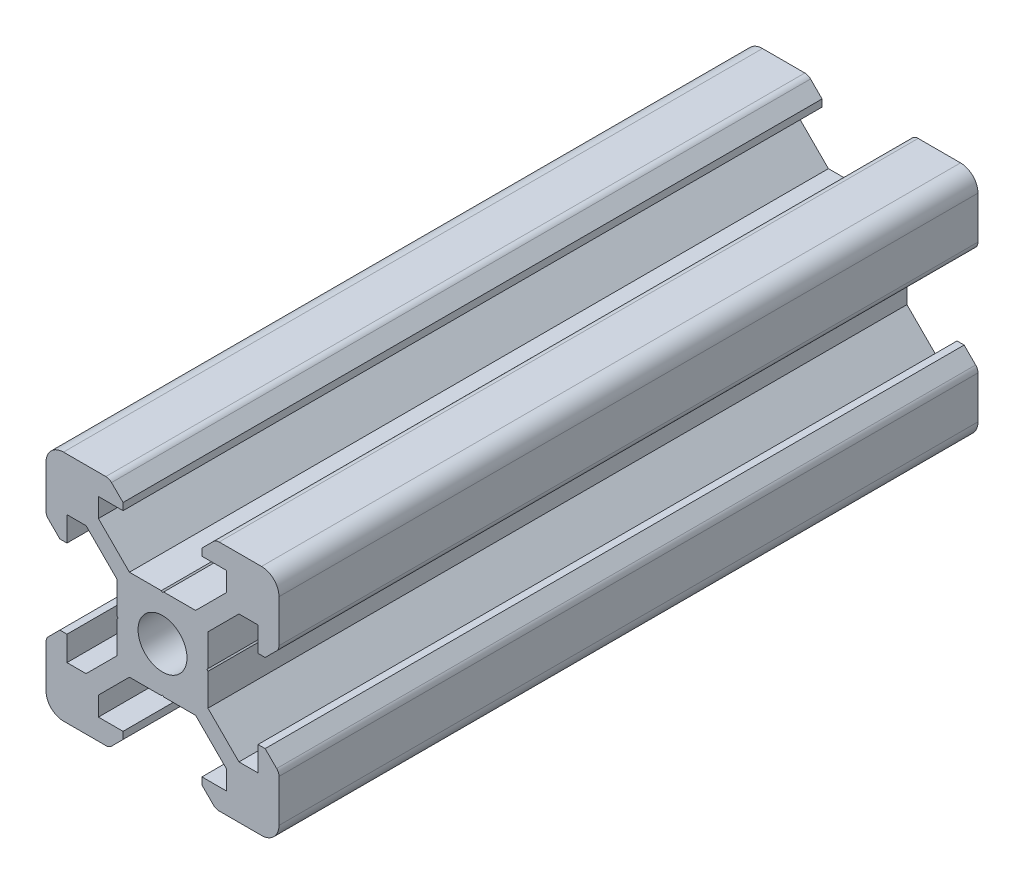
SolidWorks part; units mm, degrees
ref_plane "Front" through (0, 0, 0) normal (0, 0, 1) x (1, 0, 0)
ref_plane "Top" through (0, 0, 0) normal (0, 1, 0) x (1, 0, 0)
ref_plane "Right" through (0, 0, 0) normal (1, 0, 0) x (0, 0, -1)
sketch "Sketch1" plane through (0, 0, 0) normal (0, 0, 1) x (1, 0, 0)
  line L0 (-8.5, 10) -> (-10, 8.5) construction
  line L1 (-8.5, 10) -> (-4.8628, 10)
  line L2 (-10, 8.5) -> (-10, 4.8628)
  line L3 (-8.5, -10) -> (-4.8628, -10)
  line L4 (10, 8.5) -> (10, 4.8628)
  line L5 (-10, 10) -> (10, -10) construction
  line L6 (-10, -10) -> (10, 10) construction
  line L7 (-5.5, -8.2) -> (-3.3865, -8.2)
  line L8 (-8.2, -5.5) -> (-8.2, -3.3865)
  line L9 (-5.5, 8.2) -> (-3.3865, 8.2)
  line L10 (8.2, -5.5) -> (8.2, -3.3865)
  line L11 (-3.9005, 2.8395) -> (-6.561, 5.5)
  line L12 (-6.561, 5.5) -> (-8.2, 5.5)
  line L13 (-2.8395, -3.9005) -> (-0.1, -3.9005)
  line L14 (-3.9005, -2.8395) -> (-3.9005, -0.1)
  line L15 (-2.8395, 3.9005) -> (-0.1, 3.9005)
  line L16 (3.9005, -2.8395) -> (3.9005, -0.1)
  line L17 (-8.2, 3.3865) -> (-8.81, 3.3865)
  line L18 (-8.81, 3.3865) -> (-9.7976, 4.3741)
  line L19 (8.5, 10) -> (10, 8.5) construction
  line L20 (-2.8395, 3.9005) -> (-5.5, 6.561)
  line L21 (-5.5, 6.561) -> (-5.5, 8.2)
  line L22 (-3.3865, 8.2) -> (-3.3865, 8.81)
  line L23 (-3.3865, 8.81) -> (-4.3741, 9.7976)
  line L24 (0, 24.069) -> (0, -33.8154) construction
  line L25 (3.3865, 8.81) -> (4.3741, 9.7976)
  line L26 (3.3865, 8.2) -> (3.3865, 8.81)
  line L27 (5.5, 6.561) -> (5.5, 8.2)
  line L28 (2.8395, 3.9005) -> (5.5, 6.561)
  line L29 (3.3865, 8.2) -> (5.5, 8.2)
  line L30 (4.8628, 10) -> (8.5, 10)
  line L31 (-0.1, 3.9005) -> (0, 3.8005)
  line L32 (0.1, 3.9005) -> (0, 3.8005)
  line L33 (0.1, 3.9005) -> (2.8395, 3.9005)
  line L34 (25.9287, 0) -> (-28.3459, 0) construction
  line L35 (-0.1, -3.9005) -> (0, -3.8005)
  line L36 (0.1, -3.9005) -> (0, -3.8005)
  line L37 (0.1, -3.9005) -> (2.8395, -3.9005)
  line L38 (-3.9005, 0.1) -> (-3.8005, 0)
  line L39 (-3.8005, 0) -> (-3.9005, -0.1)
  line L40 (-3.9005, 0.1) -> (-3.9005, 2.8395)
  line L41 (3.9005, 0.1) -> (3.8005, 0)
  line L42 (3.8005, 0) -> (3.9005, -0.1)
  line L43 (3.9005, 0.1) -> (3.9005, 2.8395)
  line L44 (8.81, 3.3865) -> (9.7976, 4.3741)
  line L45 (8.2, 3.3865) -> (8.81, 3.3865)
  line L46 (6.561, 5.5) -> (8.2, 5.5)
  line L47 (3.9005, 2.8395) -> (6.561, 5.5)
  line L48 (2.8395, -3.9005) -> (5.5, -6.561)
  line L49 (3.9005, -2.8395) -> (6.561, -5.5)
  line L50 (-2.8395, -3.9005) -> (-5.5, -6.561)
  line L51 (-3.9005, -2.8395) -> (-6.561, -5.5)
  line L52 (6.561, -5.5) -> (8.2, -5.5)
  line L53 (-6.561, -5.5) -> (-8.2, -5.5)
  line L54 (-8.81, -3.3865) -> (-9.7976, -4.3741)
  line L55 (-8.2, -3.3865) -> (-8.81, -3.3865)
  line L56 (8.81, -3.3865) -> (9.7976, -4.3741)
  line L57 (8.2, -3.3865) -> (8.81, -3.3865)
  line L58 (8.2, 3.3865) -> (8.2, 5.5)
  line L59 (10, -4.8628) -> (10, -8.5)
  line L60 (-8.2, 3.3865) -> (-8.2, 5.5)
  line L61 (-10, -4.8628) -> (-10, -8.5)
  line L62 (-3.3865, -8.81) -> (-4.3741, -9.7976)
  line L63 (-3.3865, -8.2) -> (-3.3865, -8.81)
  line L64 (3.3865, -8.81) -> (4.3741, -9.7976)
  line L65 (3.3865, -8.2) -> (3.3865, -8.81)
  line L66 (-5.5, -6.561) -> (-5.5, -8.2)
  line L67 (5.5, -6.561) -> (5.5, -8.2)
  line L68 (3.3865, -8.2) -> (5.5, -8.2)
  line L69 (4.8628, -10) -> (8.5, -10)
  circle A0 centre (0, 0) radius 2.1
  arc A1 (-8.5, 10) -> (-10, 8.5) centre (-8.5, 8.5) ccw
  arc A2 (10, 8.5) -> (8.5, 10) centre (8.5, 8.5) ccw
  arc A3 (-4.3741, 9.7976) -> (-4.8628, 10) centre (-4.8628, 9.3088) ccw
  arc A4 (4.8628, 10) -> (4.3741, 9.7976) centre (4.8628, 9.3088) ccw
  arc A5 (-8.5, -10) -> (-10, -8.5) centre (-8.5, -8.5) cw
  arc A6 (9.7976, 4.3741) -> (10, 4.8628) centre (9.3088, 4.8628) ccw
  arc A7 (-10, 4.8628) -> (-9.7976, 4.3741) centre (-9.3088, 4.8628) ccw
  arc A8 (-10, -4.8628) -> (-9.7976, -4.3741) centre (-9.3088, -4.8628) cw
  arc A9 (9.7976, -4.3741) -> (10, -4.8628) centre (9.3088, -4.8628) cw
  arc A10 (10, -8.5) -> (8.5, -10) centre (8.5, -8.5) cw
  arc A11 (-4.3741, -9.7976) -> (-4.8628, -10) centre (-4.8628, -9.3088) cw
  arc A12 (4.8628, -10) -> (4.3741, -9.7976) centre (4.8628, -9.3088) cw
  point P17 (-9.25, 9.25)
  point P21 (9.25, 9.25)
  dimension "D2" = 4.2
  dimension "D4" = 1.5
  dimension "D3" = 20
  dimension "D5" = 0.529
  dimension "D6" = 6.773
  dimension "D7" = 90
  dimension "D8" = 11
  dimension "D9" = 0.61
  dimension "D10" = 0.1
  dimension "D11" = 0.1
  dimension "D12" = 0.1
  dimension "D13" = 0.1
  dimension "D14" = 5.679
  dimension "D15" = 1.639
  dimension "D16" = 1.8
  dimension "D17" = 90
  dimension "D18" = 6.773
  dimension "D19" = 90
extrude "Boss-Extrude1" add sketch "Sketch1" along normal blind 60
